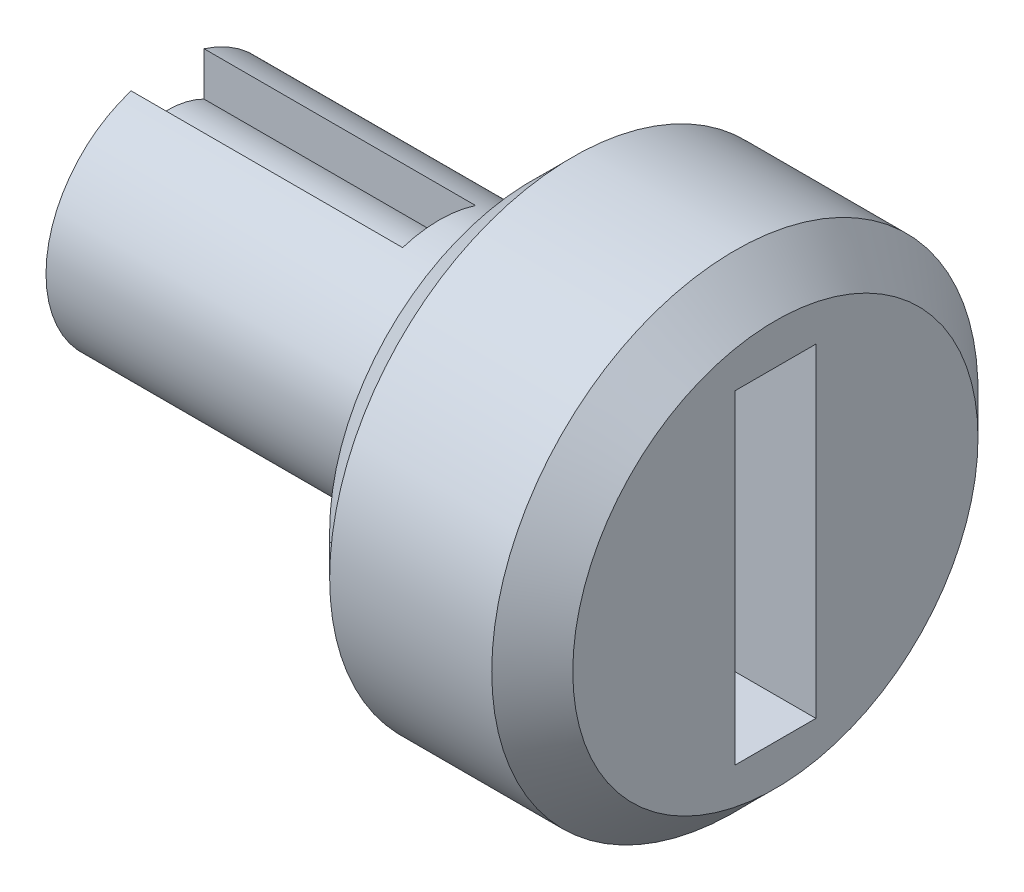
SolidWorks part; units mm, degrees
ref_plane "Front Plane" through (0, 0, 0) normal (0, 0, 1) x (1, 0, 0)
ref_plane "Top Plane" through (0, 0, 0) normal (0, 1, 0) x (1, 0, 0)
ref_plane "Right Plane" through (0, 0, 0) normal (1, 0, 0) x (0, 0, -1)
sketch "Sketch2" plane through (0, 0, 0) normal (0, 1, 0) x (1, 0, 0)
  line L0 (0, 0) -> (0, 3)
  line L1 (0, 3) -> (9, 3)
  line L2 (9, 3) -> (9, 6)
  line L3 (9, 6) -> (15, 6)
  line L4 (15, 6) -> (15, 0)
  line L5 (15, 0) -> (0, 0)
  line L6 (0, 0) -> (33.3109, 0) construction
  dimension "D1" = 15
  dimension "D2" = 6
  dimension "D3" = 6
  dimension "D4" = 12
revolve "Revolve1" add sketch "Sketch2" angle 360 about L6
sketch "Sketch3" plane through (0, 0, 0) normal (-1, 0, 0) x (0, 0, 1)
  circle A0 centre (0, 0) radius 1
  dimension "D1" = 2
extrude "Cut-Extrude1" cut sketch "Sketch3" against normal up to surface (9 mm away) up to face at (9, 0, 3)
cosmetic thread "Cosmetic Thread1" parameters "D2"=3
sketch "Sketch4" plane through (15, 0, 0) normal (1, 0, 0) x (0, 0, -1)
  line L1 (-1, -4) -> (1, -4)
  line L2 (-1, -4) -> (-1, 4)
  line L3 (-1, 4) -> (1, 4)
  line L4 (1, -4) -> (1, 4)
  line L5 (-1, -4) -> (1, 4) construction
  line L6 (-1, 4) -> (1, -4) construction
  point P0 (0, 0)
  dimension "D1" = 2
  dimension "D2" = 8
extrude "Cut-Extrude2" cut sketch "Sketch4" against normal blind 4
chamfer "Chamfer1" distance 1 angle 45 2 edges at (15, 0, 6) (9, 0, 6)
sketch "Sketch5" plane through (0, 0, 0) normal (-1, 0, 0) x (0, 0, 1)
  line L0 (-0.9, 2.3239) -> (0.9, 2.3239) construction
  line L1 (0, 2.3239) -> (0, 0) construction
  line L2 (-0.9, 2.8618) -> (-0.9, 1.7861)
  line L3 (0, 0) -> (0, -2.3239) construction
  line L4 (0.9, 2.8618) -> (0.9, 1.7861)
  line L5 (-0.9, -2.3239) -> (0.9, -2.3239) construction
  line L6 (-0.9, -1.7861) -> (-0.9, -2.8618)
  line L8 (0.9, -1.7861) -> (0.9, -2.8618)
  circle A0 centre (0, 0) radius 3 construction
  arc A1 (0.9, 2.8618) -> (-0.9, 2.8618) centre (0, 0) ccw
  arc A4 (-0.9, -2.8618) -> (0.9, -2.8618) centre (0, 0) ccw
  arc A6 (0.9, 1.7861) -> (-0.9, 1.7861) centre (0, 0) ccw
  arc A7 (-0.9, -1.7861) -> (0.9, -1.7861) centre (0, 0) ccw
  point P11 (0, -2.3239)
  dimension "D2" = 4
  dimension "D1" = 1.8
extrude "Cut-Extrude3" cut sketch "Sketch5" against normal offset from surface (6.7 mm away) 2.3 up to face at (9, 0, -5)
